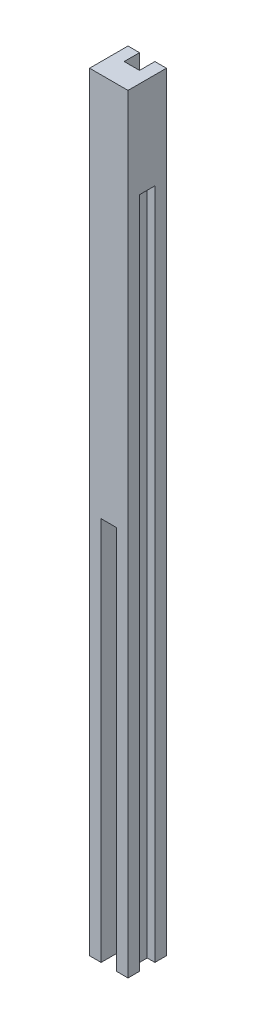
SolidWorks part; units mm, degrees
ref_plane "Front Plane" through (0, 0, 0) normal (0, 0, 1) x (1, 0, 0)
ref_plane "Top Plane" through (0, 0, 0) normal (0, 1, 0) x (1, 0, 0)
ref_plane "Right Plane" through (0, 0, 0) normal (1, 0, 0) x (0, 0, -1)
sketch "Sketch1" plane through (0, 0, 0) normal (0, 1, 0) x (1, 0, 0)
  line L1 (-43.4919, 32.6944) -> (56.5081, 32.6944)
  line L2 (-43.4919, 32.6944) -> (-43.4919, -67.3056)
  line L3 (-43.4919, -67.3056) -> (56.5081, -67.3056)
  line L4 (56.5081, 32.6944) -> (56.5081, -67.3056)
  dimension "D2" = 100
extrude "Boss-Extrude1" add sketch "Sketch1" along normal blind 2000
sketch "Sketch2" plane through (0, 0, 67.3056) normal (0, 0, 1) x (1, 0, 0)
  line L0 (-43.4919, 2000) -> (-43.4919, 0) construction
  line L1 (-13.4919, 1000) -> (26.5081, 1000)
  line L2 (-13.4919, 1000) -> (-13.4919, 0)
  line L3 (-13.4919, 0) -> (26.5081, 0)
  line L4 (26.5081, 1000) -> (26.5081, 0)
  line L5 (-43.4919, 0) -> (56.5081, 0) construction
  dimension "D1" = 1000
  dimension "D2" = 40
  dimension "D3" = 30
  dimension "D4" = 0
extrude "Cut-Extrude1" cut sketch "Sketch2" against normal blind 40 contours L1 L4 L3 L2
sketch "Sketch3" plane through (0, 0, -32.6944) normal (0, 0, -1) x (-1, 0, 0)
  line L0 (-56.5081, 2000) -> (43.4919, 2000) construction
  line L1 (-26.5081, 2000) -> (13.4919, 2000)
  line L2 (-26.5081, 2000) -> (-26.5081, 1000)
  line L3 (-26.5081, 1000) -> (13.4919, 1000)
  line L4 (13.4919, 2000) -> (13.4919, 1000)
  line L5 (-56.5081, 2000) -> (-56.5081, 0) construction
  dimension "D1" = 40
  dimension "D2" = 30
  dimension "D3" = 1000
extrude "Cut-Extrude2" cut sketch "Sketch3" against normal blind 40 contours L2 L1 L4 L3
sketch "Sketch4" plane through (56.5081, 0, 0) normal (1, 0, 0) x (0, 0, -1)
  line L0 (-67.3056, 0) -> (32.6944, 0) construction
  line L1 (-37.3056, 1750) -> (2.6944, 1750)
  line L2 (-37.3056, 1750) -> (-37.3056, 0)
  line L3 (-37.3056, 0) -> (2.6944, 0)
  line L4 (2.6944, 1750) -> (2.6944, 0)
  line L6 (-67.3056, 2000) -> (-67.3056, 0) construction
  dimension "D1" = 40
  dimension "D2" = 0
  dimension "D3" = 1750
  dimension "D4" = 30
sketch "Sketch5" plane through (-43.4919, 0, 0) normal (-1, 0, 0) x (0, 0, 1)
  line L0 (-32.6944, 0) -> (67.3056, 0) construction
  line L1 (-2.6944, 1750) -> (37.3056, 1750)
  line L2 (-2.6944, 1750) -> (-2.6944, 0)
  line L3 (-2.6944, 0) -> (37.3056, 0)
  line L4 (37.3056, 1750) -> (37.3056, 0)
  line L5 (-32.6944, 2000) -> (-32.6944, 0) construction
  dimension "D1" = 40
  dimension "D2" = 0
  dimension "D3" = 1750
  dimension "D4" = 30
extrude "Cut-Extrude3" cut sketch "Sketch4" against normal blind 20 contours L4 L3 L2 L1
extrude "Cut-Extrude4" cut sketch "Sketch5" against normal blind 20 contours L4 L3 L2 L1
equation "\"BeamWidth\"= 100"
equation "\"BeamLength\"= 100"
equation "\"BeamHeight\"= 2000"
equation "\"D1@Sketch1\"=\"BeamWidth\""
equation "\"D2@Sketch1\"=\"BeamLength\""
equation "\"D1@Boss-Extrude1\"=\"BeamHeight\""
equation "\"LegHeight\"= 1000"
equation "\"LegScannerWidth\"= 40"
equation "\"D1@Sketch2\"=\"LegHeight\""
equation "\"D2@Sketch2\"=\"LegScannerWidth\""
equation "\"D3@Sketch2\"=(\"BeamWidth\"-\"LegScannerWidth\")/2"
equation "\"LegScannerDepth\"= 40"
equation "\"D1@Cut-Extrude1\"=\"LegScannerDepth\""
equation "\"D1@Sketch3\"=\"LegScannerWidth\""
equation "\"D2@Sketch3\"=(\"BeamWidth\"-\"LegScannerWidth\")/2"
equation "\"D3@Sketch3\"=\"LegHeight\""
equation "\"D1@Cut-Extrude2\"=\"LegScannerDepth\""
equation "\"SideRailLength\"= 1750"
equation "\"D1@Sketch4\"=\"LegScannerWidth\""
equation "\"D3@Sketch4\"=\"SideRailLength\""
equation "\"D1@Sketch5\"=\"LegScannerWidth\""
equation "\"D3@Sketch5\"=\"SideRailLength\""
equation "\"D4@Sketch5\"=(\"BeamLength\"-\"LegScannerWidth\")/2"
equation "\"D4@Sketch4\"=(\"BeamLength\"-\"LegScannerWidth\")/2"
equation "\"BottomScannerDepth\"=20"
equation "\"D1@Cut-Extrude3\"=\"BottomScannerDepth\""
equation "\"D1@Cut-Extrude4\"=\"BottomScannerDepth\""
